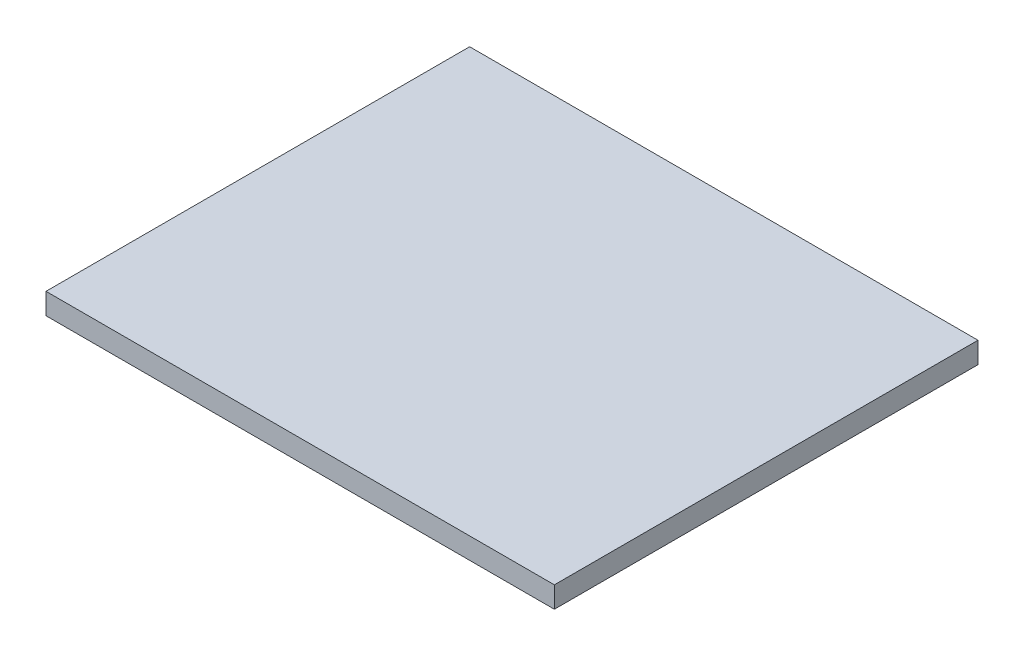
SolidWorks part; units mm, degrees
ref_plane "Front Plane" through (0, 0, 0) normal (0, 0, 1) x (1, 0, 0)
ref_plane "Top Plane" through (0, 0, 0) normal (0, 1, 0) x (1, 0, 0)
ref_plane "Right Plane" through (0, 0, 0) normal (1, 0, 0) x (0, 0, -1)
sketch "Sketch1" plane through (0, 0, 0) normal (0, 1, 0) x (1, 0, 0)
  line L1 (-60, -50) -> (60, -50)
  line L2 (-60, -50) -> (-60, 50)
  line L3 (-60, 50) -> (60, 50)
  line L4 (60, -50) -> (60, 50)
  line L5 (0, 50) -> (0, -50) construction
  line L6 (-60, 0) -> (60, 0) construction
  point P0 (0, 0)
  dimension "D1" = 120
  dimension "D2" = 100
extrude "Boss-Extrude1" add sketch "Sketch1" along normal blind 5
